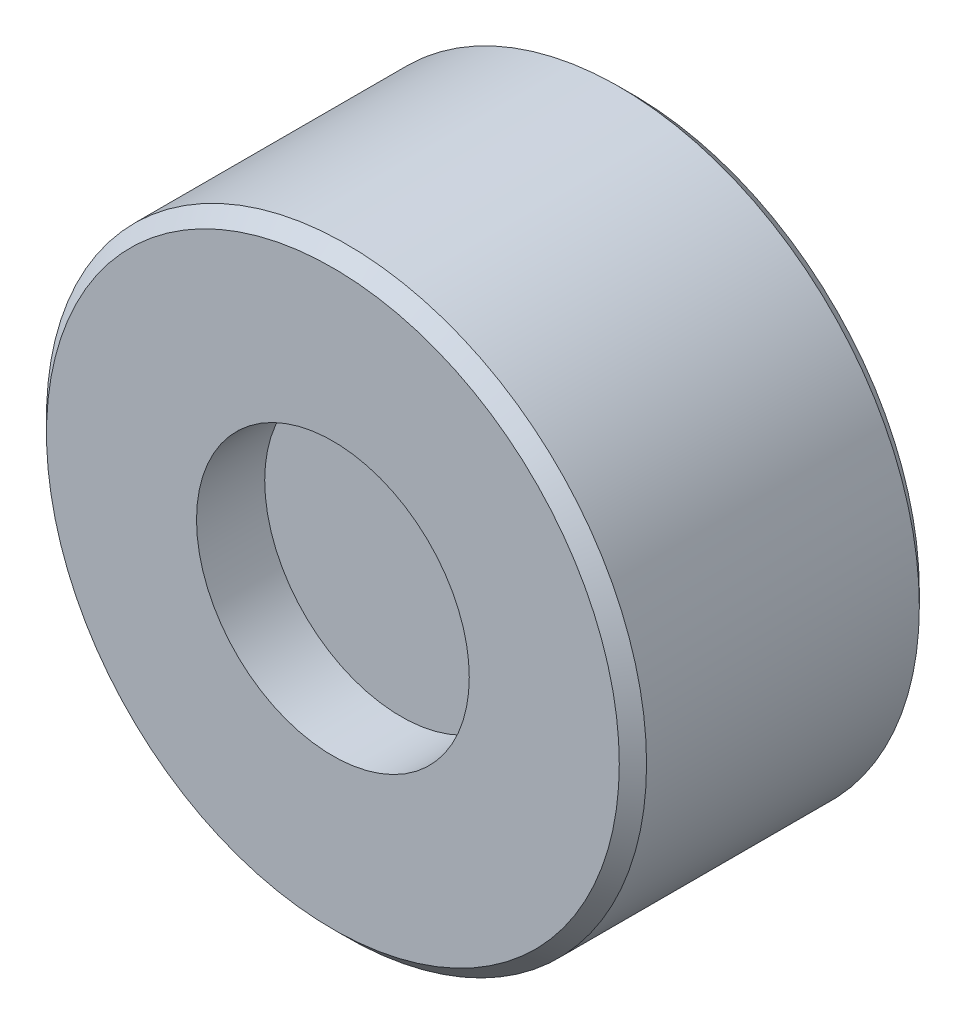
SolidWorks part; units mm, degrees
ref_plane "Front" through (0, 0, 0) normal (0, 0, 1) x (1, 0, 0)
ref_plane "Top" through (0, 0, 0) normal (0, 1, 0) x (1, 0, 0)
ref_plane "Right" through (0, 0, 0) normal (1, 0, 0) x (0, 0, -1)
sketch "草图1" plane through (0, 0, 0) normal (0, 0, 1) x (1, 0, 0)
  circle A0 centre (0, 0) radius 22
  dimension "D1" = 44
extrude "凸台-拉伸1" add sketch "草图1" along normal blind 22
sketch "草图2" plane through (0, 0, 22) normal (0, 0, 1) x (1, 0, 0)
  circle A0 centre (0, 0) radius 10
  dimension "D1" = 20
extrude "切除-拉伸1" cut sketch "草图2" against normal blind 5 contours A0
chamfer "倒角1" distance 1 angle 45 2 edges at (22, 0, 22) (22, 0, 0)
sketch "草图3" plane through (0, 0, 0) normal (0, 0, -1) x (-1, 0, 0)
  circle A0 centre (0, 0) radius 18.8183
  circle A1 centre (0, 18.8183) radius 0.911
extrude "切除-拉伸2" cut sketch "草图3" against normal blind 1 contours A1
chamfer "倒角2" distance 0.9 angle 45 1 edges at (-0.911, 18.8183, 1)
